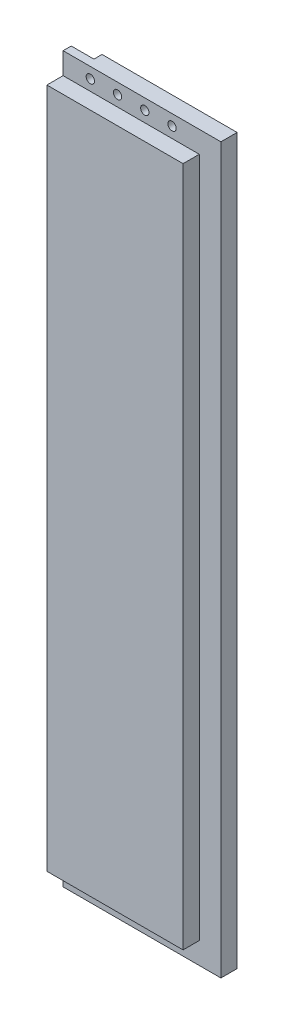
SolidWorks part; units mm, degrees
ref_plane "Front Plane" through (0, 0, 0) normal (0, 0, 1) x (1, 0, 0)
ref_plane "Top Plane" through (0, 0, 0) normal (0, 1, 0) x (1, 0, 0)
ref_plane "Right Plane" through (0, 0, 0) normal (1, 0, 0) x (0, 0, -1)
sketch "Sketch1" plane through (0, 0, 0) normal (0, 1, 0) x (1, 0, 0)
  line L1 (-67.9096, 3.3167) -> (24.7904, 3.3167)
  line L2 (-67.9096, 3.3167) -> (-67.9096, -15.7333)
  line L3 (-67.9096, -15.7333) -> (24.7904, -15.7333)
  line L4 (24.7904, 3.3167) -> (24.7904, -15.7333)
  dimension "D1" = 19.05
  dimension "D2" = 92.7
extrude "Boss-Extrude1" add sketch "Sketch1" along normal blind 425.45
sketch "Sketch2" plane through (24.7904, 0, 0) normal (1, 0, 0) x (0, 0, -1)
  line L0 (-15.7333, 425.45) -> (-15.7333, 0) construction
  line L1 (-15.7333, 425.45) -> (-6.2083, 425.45)
  line L2 (-15.7333, 425.45) -> (-15.7333, 412.75)
  line L3 (-15.7333, 412.75) -> (-6.2083, 412.75)
  line L4 (-6.2083, 425.45) -> (-6.2083, 412.75)
  line L5 (-15.7333, 12.7) -> (-6.2083, 12.7)
  line L6 (-15.7333, 12.7) -> (-15.7333, 0)
  line L7 (-15.7333, 0) -> (-6.2083, 0)
  line L8 (-6.2083, 12.7) -> (-6.2083, 0)
  line L9 (-15.7333, 0) -> (3.3167, 0) construction
  dimension "D1" = 9.525
  dimension "D2" = 12.7
  dimension "D3" = 9.525
  dimension "D4" = 12.7
extrude "Cut-Extrude1" cut sketch "Sketch2" against normal through all
sketch "Sketch3" plane through (0, 12.7, 0) normal (0, -1, 0) x (1, 0, 0)
  line L0 (-67.9096, 15.7333) -> (24.7904, 15.7333) construction
  line L1 (12.0904, 15.7333) -> (24.7904, 15.7333)
  line L2 (12.0904, 15.7333) -> (12.0904, 6.2083)
  line L3 (12.0904, 6.2083) -> (24.7904, 6.2083)
  line L4 (24.7904, 15.7333) -> (24.7904, 6.2083)
  line L5 (-67.9096, 6.2083) -> (24.7904, 6.2083) construction
  dimension "D1" = 12.7
extrude "Cut-Extrude2" cut sketch "Sketch3" against normal through all
hole_wizard "#8 Clearance Hole1" positions "Sketch5" profile "Sketch4" hole size "#8" standard "ANSI Inch" end condition through all
sketch "Sketch5" plane through (0, 0, 6.2083) normal (0, 0, 1) x (1, 0, 0)
  line L0 (-67.9096, 12.7) -> (12.0904, 12.7) construction
  line L1 (-67.9096, 412.75) -> (12.0904, 412.75) construction
  line L2 (12.0904, 412.75) -> (12.0904, 12.7) construction
  point P0 (-51.9176, 6.35)
  point P2 (-35.9156, 6.35)
  point P4 (-19.9136, 6.35)
  point P6 (-3.9116, 6.35)
  point P8 (-51.9176, 419.1)
  point P10 (-35.9156, 419.1)
  point P12 (-19.9136, 419.1)
  point P14 (-3.9116, 419.1)
other "AlignGroup1" parameters "D1"=5.5565, "D2"=80, "D3"=17.932, "D4"=16.002, "D5"=32.004, "D6"=48.006, "D7"=64.008
sketch "Sketch4" plane through (-51.9176, 6.35, 6.2083) normal (1, 0, 0) x (0, -1, 0)
  line L0 (0, 0) -> (0, 9.525)
  line L1 (0, 9.525) -> (2.4574, 9.525)
  line L2 (2.4574, 9.525) -> (2.4574, 0)
  line L5 (2.4574, 0) -> (0, 0)
  line L11 (0, -6.35) -> (0, 107.95) construction
  dimension "Thru Hole Dia." = 4.9149
  dimension "Thru Hole Depth" = 9.525
ref_plane "Plane1" through (-67.9096, 425.45, -3.3167) normal (0, -1, 0) x (-1, 0, 0)
sketch "Sketch6" plane through (-67.9096, 425.45, -3.3167) normal (0, -1, 0) x (1, 0, 0)
  line L1 (0, 0) -> (13.335, 0)
  line L2 (0, 0) -> (0, 4.7498)
  line L3 (0, 4.7498) -> (13.335, 4.7498)
  line L4 (13.335, 0) -> (13.335, 4.7498)
  dimension "D1" = 13.335
  dimension "D2" = 4.7498
extrude "Cut-Extrude5" cut sketch "Sketch6" along normal through all
